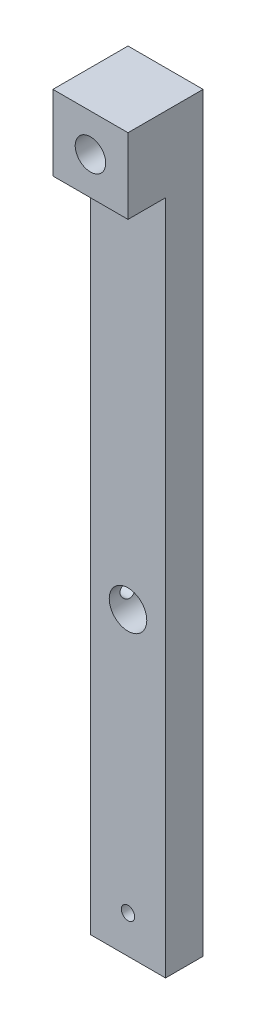
SolidWorks part; units mm, degrees
material "1060 Alloy"
ref_plane "Front Plane" through (0, 0, 0) normal (0, 0, 1) x (1, 0, 0)
ref_plane "Top Plane" through (0, 0, 0) normal (0, 1, 0) x (1, 0, 0)
ref_plane "Right Plane" through (0, 0, 0) normal (1, 0, 0) x (0, 0, -1)
sketch "Sketch1" plane through (0, 0, 0) normal (0, 0, 1) x (1, 0, 0)
  line L1 (-6.35, 63.5) -> (6.35, 63.5)
  line L2 (-6.35, 63.5) -> (-6.35, -63.5)
  line L3 (-6.35, -63.5) -> (6.35, -63.5)
  line L4 (6.35, 63.5) -> (6.35, -63.5)
  line L5 (-6.35, 63.5) -> (6.35, -63.5) construction
  line L6 (-6.35, -63.5) -> (6.35, 63.5) construction
  point P0 (0, 0)
  dimension "D1" = 12.7
  dimension "D2" = 127
extrude "Boss-Extrude1" add sketch "Sketch1" along normal blind 6.35
sketch "Sketch3" plane through (0, 0, 6.35) normal (0, 0, 1) x (1, 0, 0)
  line L0 (6.35, -63.5) -> (6.35, 63.5) construction
  line L1 (-6.35, 63.5) -> (6.35, 63.5)
  line L2 (-6.35, 63.5) -> (-6.35, 50.8)
  line L3 (-6.35, 50.8) -> (6.35, 50.8)
  line L4 (6.35, 63.5) -> (6.35, 50.8)
  dimension "D1" = 12.7
extrude "Boss-Extrude2" add sketch "Sketch3" along normal blind 6.35
sketch "Sketch4" plane through (0, 0, 0) normal (0, 0, -1) x (-1, 0, 0)
  line L0 (0, 63.5) -> (0, -63.5) construction
  line L1 (-6.35, 63.5) -> (6.35, 63.5) construction
  line L2 (6.35, -63.5) -> (-6.35, -63.5) construction
  line L3 (-6.35, 63.5) -> (6.35, 63.5) construction
  circle A0 centre (0, -12.7) radius 3.175
  dimension "D1" = 6.35
  dimension "D2" = 76.2
extrude "Cut-Extrude1" cut sketch "Sketch4" against normal through all
hole_wizard "#4-40 Tapped Hole1" positions "3DSketch1" profile "Sketch5" tap size "#4-40" standard "Ansi Inch" end condition through all
sketch3d "3DSketch1"
  line L0 (0, 63.5, 0) -> (0, -63.5, 0) construction
  line L1 (6.35, 63.5, 0) -> (-6.35, 63.5, 0) construction
  line L2 (-6.35, -63.5, 0) -> (6.35, -63.5, 0) construction
  point P0 (0, -57.15, 0)
  dimension "D1" = 6.35
cosmetic thread "Hole Thread1" parameters "D2"=2.8448
sketch "Sketch5" plane through (0, -57.15, 0) normal (1, 0, 0) x (0, 1, 0)
  line L0 (0, 0) -> (0, 12.7)
  line L1 (0, 12.7) -> (1.1303, 12.7)
  line L2 (1.1303, 12.7) -> (1.1303, 0)
  line L5 (1.1303, 0) -> (0, 0)
  line L11 (0, -6.35) -> (0, 107.95) construction
  dimension "Thru Tap Drill Dia." = 2.2606
  dimension "Thru Tap Drill Depth" = 12.7
sketch "Sketch6" plane through (0, 0, 12.7) normal (0, 0, 1) x (1, 0, 0)
  line L0 (0, 63.5) -> (0, 50.8) construction
  line L1 (6.35, 63.5) -> (-6.35, 63.5) construction
  line L2 (-6.35, 50.8) -> (6.35, 50.8) construction
  circle A0 centre (0, 57.15) radius 330.2
  circle A1 centre (0, 57.15) radius 2.5797
  dimension "D1" = 5.1594
extrude "Cut-Extrude3" cut sketch "Sketch6" against normal through all flip side to cut
hole_wizard "#6-32 Tapped Hole2" [suppressed] positions "Sketch10" profile "Sketch9" tap size "#6-32" standard "Ansi Inch"
sketch "Sketch10" plane through (6.35, 0, 0) normal (1, 0, 0) x (0, 0, -1)
  line L0 (-3.175, -9.525) -> (-3.175, -15.875) construction
  line L1 (0, -9.525) -> (-6.35, -9.525) construction
  line L2 (-6.35, -15.875) -> (0, -15.875) construction
  point P0 (-3.175, -12.7)
sketch "Sketch9" plane through (6.35, -12.7, 3.175) normal (0, 1, 0) x (0, 0, -1)
  line L0 (0, 0) -> (0, 7.1617)
  line L1 (0, 7.1617) -> (1.3525, 6.349)
  line L2 (1.3525, 6.349) -> (1.3525, 0)
  line L5 (1.3525, 0) -> (0, 0)
  line L10 (0, 7.1617) -> (-1.3526, 6.349) construction
  line L11 (0, -6.35) -> (0, 107.95) construction
  dimension "Tap Drill Dia." = 2.7051
  dimension "Tap Drill Depth" = 6.349
  dimension "Drill Angle" = 118
cosmetic thread "Hole Thread3" [suppressed] parameters "D1"=3.4775, "D2"=3.5052
hole_wizard "#6-32 Tapped Hole1" positions "Sketch8" profile "Sketch7" tap size "#6-32" standard "Ansi Inch"
sketch "Sketch8" plane through (-6.35, 0, 0) normal (-1, 0, 0) x (0, 0, 1)
  line L4 (3.175, -9.525) -> (3.175, -15.875) construction
  line L5 (6.35, -9.525) -> (0, -9.525) construction
  line L6 (0, -15.875) -> (6.35, -15.875) construction
  point P0 (3.175, -12.7)
sketch "Sketch7" plane through (-6.35, -12.7, 3.175) normal (0, 1, 0) x (0, 0, 1)
  line L0 (0, 0) -> (0, 7.1617)
  line L1 (0, 7.1617) -> (1.3525, 6.349)
  line L2 (1.3525, 6.349) -> (1.3525, 0)
  line L5 (1.3525, 0) -> (0, 0)
  line L10 (0, 7.1617) -> (-1.3526, 6.349) construction
  line L11 (0, -6.35) -> (0, 107.95) construction
  dimension "Tap Drill Dia." = 2.7051
  dimension "Tap Drill Depth" = 6.349
  dimension "Drill Angle" = 118
cosmetic thread "Hole Thread2" parameters "D1"=7.0104, "D2"=3.5052
